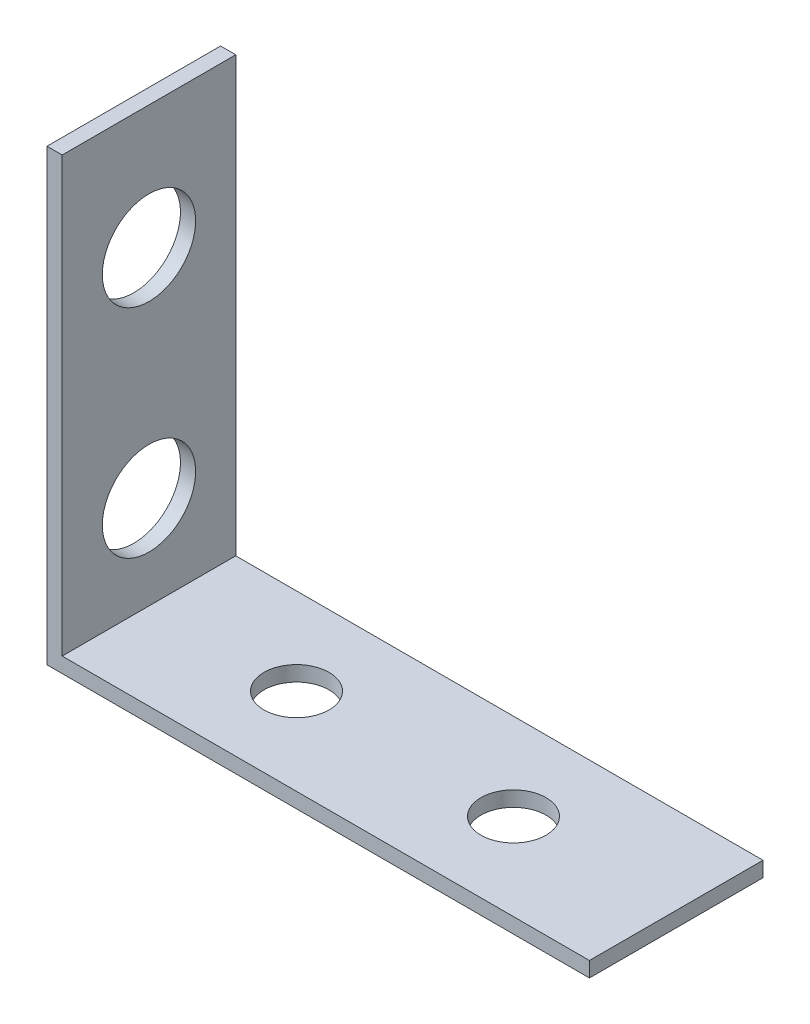
SolidWorks part; units mm, degrees
ref_plane "Front Plane" through (0, 0, 0) normal (0, 0, 1) x (1, 0, 0)
ref_plane "Top Plane" through (0, 0, 0) normal (0, 1, 0) x (1, 0, 0)
ref_plane "Right Plane" through (0, 0, 0) normal (1, 0, 0) x (0, 0, -1)
sketch "Sketch1" plane through (0, 0, 0) normal (0, 1, 0) x (1, 0, 0)
  line L0 (-12.5, 4) -> (12.5, 4) construction
  line L1 (-12.5, 8) -> (12.5, 8)
  line L2 (-12.5, 8) -> (-12.5, 0)
  line L3 (-12.5, 0) -> (12.5, 0)
  line L4 (12.5, 8) -> (12.5, 0)
  line L5 (0, 8) -> (0, 0) construction
  circle A0 centre (-5, 4) radius 1.5
  circle A1 centre (5, 4) radius 1.5
  point P4 (0, 0)
  point P6 (20, 2.6158)
  point P15 (0, 0)
  point P16 (-20, 2.0054)
  dimension "D3" = 3
  dimension "D1" = 8
  dimension "D2" = 25
  dimension "D4" = 7.5
  dimension "D5" = 4
extrude "Boss-Extrude1" add sketch "Sketch1" along normal blind 0.7 contours L0 L2 L3 L5 A0 | L0 L5 L3 L4 A1 | L5 L0 A1 L4 L1 | L2 L0 A0 L5 L1
sketch "Sketch3" plane through (0, 0.7, 0) normal (0, 1, 0) x (1, 0, 0)
  line L0 (-12.5, 0) -> (12.5, 0) construction
  line L1 (-12.5, 0) -> (-11.8, 0)
  line L2 (-12.5, 0) -> (-12.5, 8)
  line L3 (-12.5, 8) -> (-11.8, 8)
  line L4 (-11.8, 0) -> (-11.8, 8)
  line L5 (-12.5, 8) -> (-12.5, 0) construction
  point P8 (-20, 10)
  point P10 (-20, 12.6)
  point P11 (20, 0)
  point P12 (20, 0)
  dimension "D1" = 0.7
extrude "Boss-Extrude3" add sketch "Sketch3" along normal blind 20
sketch "Sketch4" plane through (-12.5, 0, 0) normal (-1, 0, 0) x (0, 0, 1)
  line L0 (-4, 20.7) -> (-4, 0) construction
  line L1 (-8, 20.7) -> (0, 20.7) construction
  line L2 (-8, 0) -> (0, 0) construction
  circle A0 centre (-4, 5) radius 2.15
  circle A1 centre (-4, 15) radius 2.15
  dimension "D4" = 4.3
  dimension "D1" = 4
  dimension "D2" = 5
  dimension "D3" = 10
extrude "Cut-Extrude1" cut sketch "Sketch4" against normal through all
